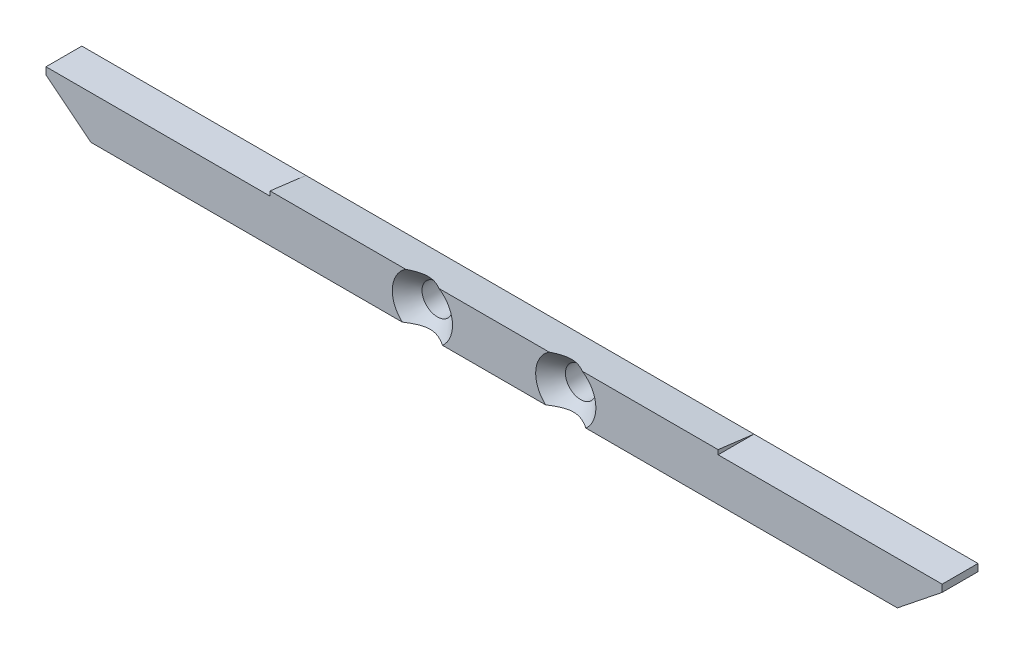
SolidWorks part; units mm, degrees
ref_plane "前视基准面" through (0, 0, 0) normal (0, 0, 1) x (1, 0, 0)
ref_plane "上视基准面" through (0, 0, 0) normal (0, 1, 0) x (1, 0, 0)
ref_plane "右视基准面" through (0, 0, 0) normal (1, 0, 0) x (0, 0, -1)
sketch "草图1" plane through (0, 0, 0) normal (0, 0, 1) x (1, 0, 0)
  line L1 (0, 0) -> (100, 0)
  line L2 (0, 0) -> (0, 5.3)
  line L3 (0, 5.3) -> (100, 5.3)
  line L4 (100, 0) -> (100, 5.3)
  dimension "D1" = 5.3
  dimension "D2" = 100
extrude "凸台-拉伸1" add sketch "草图1" along normal blind 4
sketch "草图2" plane through (100, 0, 0) normal (1, 0, 0) x (0, 0, -1)
  line L0 (-4, 5.3) -> (0, 5.3)
  line L1 (0, 5.3) -> (0, 4.8)
  line L2 (0, 0) -> (0, 5.3) construction
  line L3 (0, 4.8) -> (-4, 5.3)
  dimension "D1" = 0.5
extrude "切除-拉伸1" cut sketch "草图2" against normal through all
sketch "草图3" plane through (0, 0, 4) normal (0, 0, 1) x (1, 0, 0)
  line L0 (0, 2.5) -> (40, 2.5) construction
  line L3 (50, 5.3) -> (50, 0) construction
  line L4 (100, 5.3) -> (0, 5.3) construction
  line L5 (0, 0) -> (100, 0) construction
  circle A0 centre (42, 2.5) radius 1.5
  circle A1 centre (58, 2.5) radius 1.5
  dimension "D2" = 3
  dimension "D1" = 2.5
  dimension "D3" = 16
extrude "切除-拉伸2" cut sketch "草图3" against normal through all
hole_wizard "M3 六角凹锥坑螺钉的锥形沉头孔1" positions "3D草图1" profile "草图4" countersink size "M3" standard "ISO" end condition through all
sketch3d "3D草图1"
  line L0 (42, 2.5, 0) -> (42, 2.5, 4) construction
  line L1 (58, 2.5, 0) -> (58, 2.5, 4) construction
  point P0 (42, 2.5, 4)
  point P4 (58, 2.5, 4)
sketch "草图4" plane through (42, 2.5, 4) normal (1, 0, 0) x (0, -1, 0)
  line L0 (0, 0) -> (0, 4)
  line L1 (0, 4) -> (1.7, 4)
  line L2 (1.7, 4) -> (1.7, 1.66)
  line L3 (1.7, 1.66) -> (3.36, 0)
  line L5 (3.36, 0) -> (0, 0)
  line L6 (-1.7, 1.66) -> (-3.36, 0) construction
  line L11 (0, -6.35) -> (0, 107.95) construction
  dimension "通孔孔直径" = 3.4
  dimension "通孔孔深度" = 4
  dimension "近端锥形沉头孔直径" = 6.72
  dimension "近端锥形沉头孔角度" = 90
sketch "草图6" plane through (0, 0, 4) normal (0, 0, 1) x (1, 0, 0)
  line L0 (0, 4) -> (5, 0)
  line L1 (0, 5.3) -> (0, 0) construction
  line L2 (0, 0) -> (39.7551, 0) construction
  line L3 (5, 0) -> (0, 0)
  line L4 (0, 0) -> (0, 4)
  line L5 (50, 5.3) -> (50, -49994.7) construction
  line L6 (56.1427, 5.3) -> (43.8573, 5.3) construction
  line L7 (44.2449, 0) -> (55.7551, 0) construction
  line L8 (100, 0) -> (100, 4)
  line L9 (95, 0) -> (100, 0)
  line L10 (100, 4) -> (95, 0)
  point P12 (50, 5.3)
  point P15 (50, 0)
  dimension "D1" = 5
  dimension "D2" = 4
extrude "切除-拉伸3" cut sketch "草图6" against normal through all
sketch "草图7" plane through (100, 0, 0) normal (1, 0, 0) x (0, 0, -1)
  line L0 (-4, 5.3) -> (0, 4.8)
  line L1 (0, 4.8) -> (-4, 4.8)
  line L2 (-4, 4) -> (-4, 5.3) construction
  line L3 (-4, 4.8) -> (-4, 5.3)
extrude "切除-拉伸4" cut sketch "草图7" against normal blind 25
sketch "草图8" plane through (0, 0, 0) normal (-1, 0, 0) x (0, 0, 1)
  line L0 (0, 4.8) -> (4, 4.8)
  line L1 (4, 4.8) -> (4, 5.3)
  line L2 (4, 5.3) -> (0, 4.8)
extrude "切除-拉伸5" cut sketch "草图8" against normal blind 25
